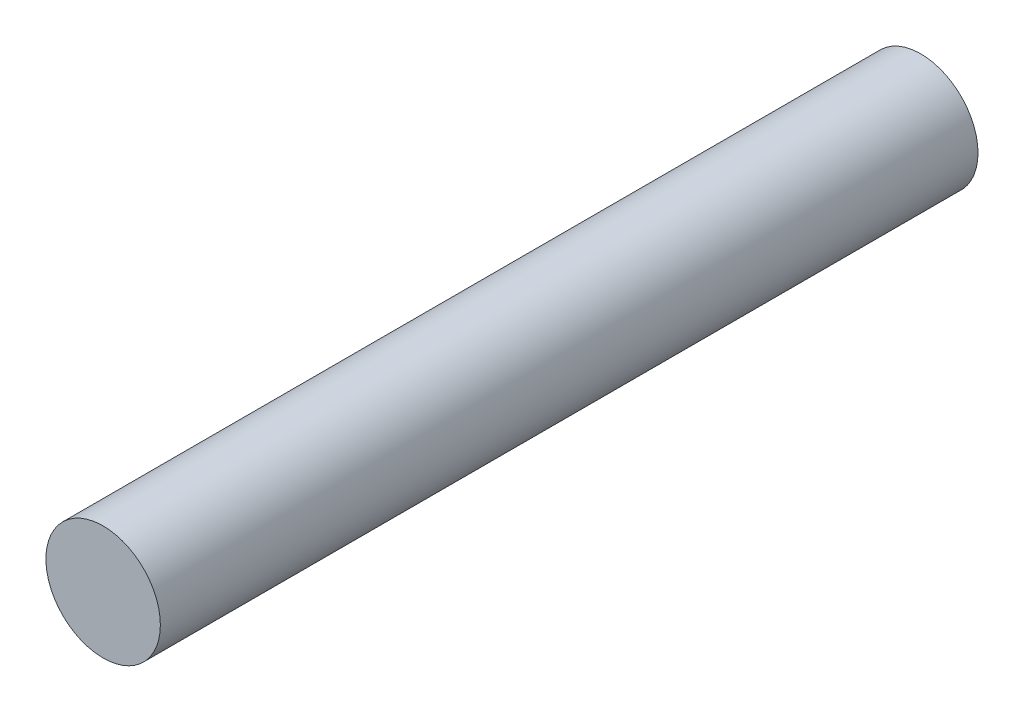
SolidWorks part; units mm, degrees
ref_plane "Plan de face" through (0, 0, 0) normal (0, 0, 1) x (1, 0, 0)
ref_plane "Plan de dessus" through (0, 0, 0) normal (0, 1, 0) x (1, 0, 0)
ref_plane "Plan de droite" through (0, 0, 0) normal (1, 0, 0) x (0, 0, -1)
sketch "Esquisse1" plane through (0, 0, 0) normal (0, 0, 1) x (1, 0, 0)
  circle A0 centre (-5.591, 1.712) radius 1.05
  dimension "D1" = 2.1
extrude "Boss.-Extru.1" add sketch "Esquisse1" along normal blind 15
